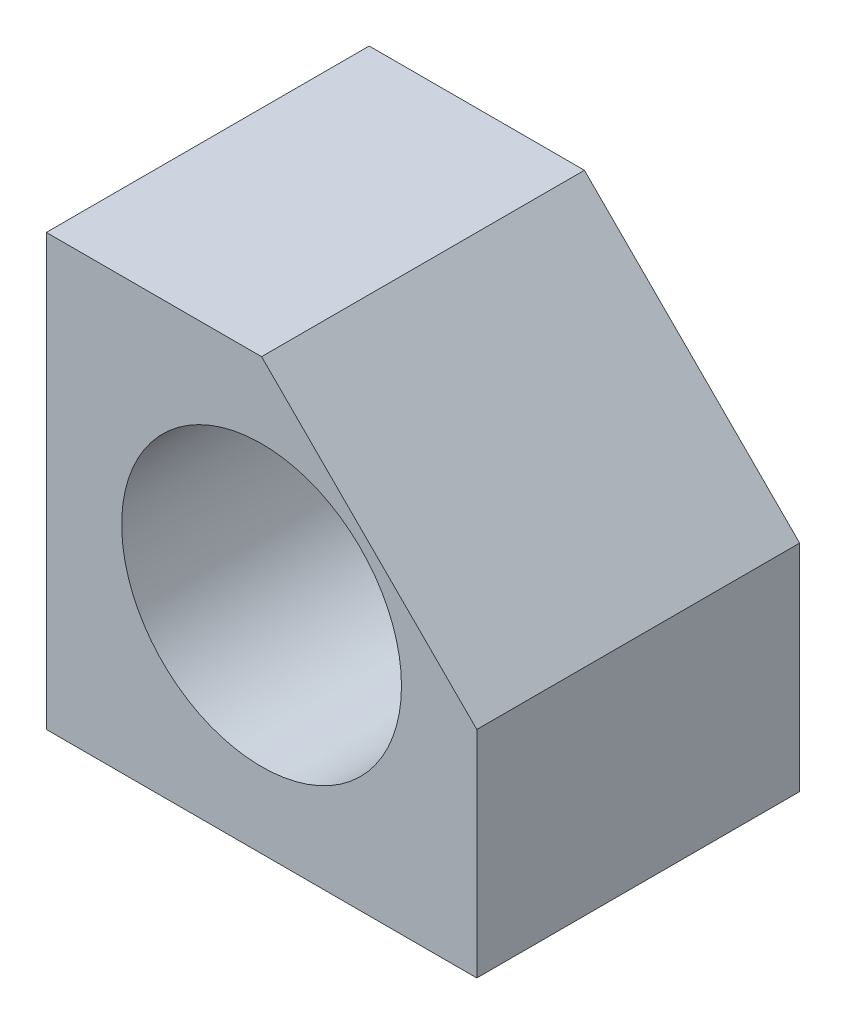
SolidWorks part; units mm, degrees
ref_plane "Front Plane" through (0, 0, 0) normal (0, 0, 1) x (1, 0, 0)
ref_plane "Top Plane" through (0, 0, 0) normal (0, 1, 0) x (1, 0, 0)
ref_plane "Right Plane" through (0, 0, 0) normal (1, 0, 0) x (0, 0, -1)
sketch "Sketch1" plane through (0, 0, 0) normal (0, 0, 1) x (1, 0, 0)
  line L0 (165.27, -84.42) -> (169.27, -84.42)
  line L1 (169.27, -60.42) -> (167.27, -60.42) construction
  line L4 (169.27, -62.42) -> (169.27, -58.42)
  line L8 (165.27, -58.42) -> (169.27, -58.42)
  line L9 (165.27, -58.42) -> (165.27, -62.42)
  line L10 (169.27, -58.42) -> (165.27, -58.42)
  line L11 (169.27, -58.42) -> (169.27, -62.42)
  line L12 (169.27, -62.42) -> (165.27, -62.42)
  line L13 (165.27, -58.42) -> (165.27, -62.42)
  circle A1 centre (167.27, -82.42) radius 1.3
  circle A2 centre (167.27, -60.42) radius 1.3
  dimension "D3" = 2.6
  dimension "D1" = 4
  dimension "D2" = 2
extrude "Boss-Extrude1" add sketch "Sketch1" along normal blind 3
chamfer "Chamfer1" distance 2 angle 45 1 edges at (169.27, -58.42, 1.5)
